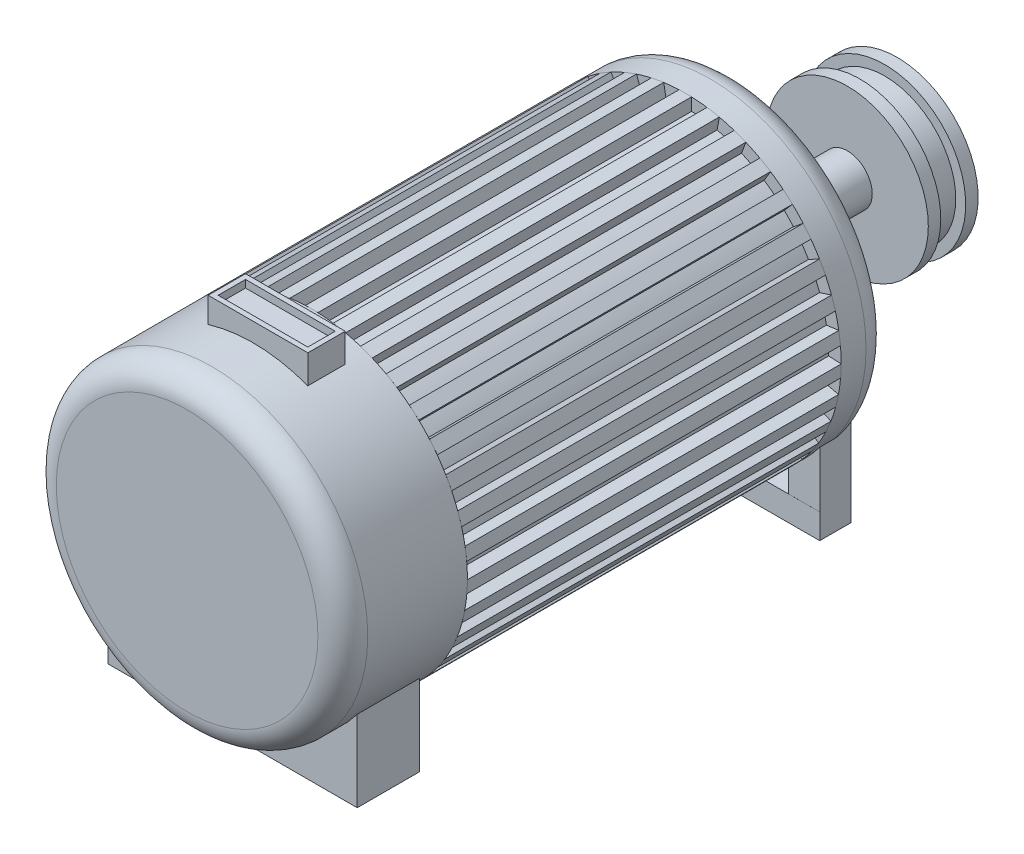
SolidWorks part; units mm, degrees
ref_plane "Front Plane" through (0, 0, 0) normal (0, 0, 1) x (1, 0, 0)
ref_plane "Top Plane" through (0, 0, 0) normal (0, 1, 0) x (1, 0, 0)
ref_plane "Right Plane" through (0, 0, 0) normal (1, 0, 0) x (0, 0, -1)
sketch "Sketch1" plane through (0, 0, 0) normal (0, 0, 1) x (1, 0, 0)
  line L0 (0.87, 6.1942) -> (1.362, 6.1049)
  line L1 (-0.25, 6.25) -> (0.25, 6.25)
  line L2 (0.25, 6.25) -> (0.25, 5.7446)
  line L3 (-0.25, 6.25) -> (-0.25, 5.7446)
  line L4 (0.87, 6.1942) -> (0.7797, 5.6969)
  line L5 (1.362, 6.1049) -> (1.2717, 5.6076)
  line L6 (1.962, 5.9393) -> (2.4302, 5.7636)
  line L7 (1.962, 5.9393) -> (1.7844, 5.4661)
  line L8 (2.4302, 5.7636) -> (2.2526, 5.2904)
  line L9 (2.991, 5.4935) -> (3.4202, 5.2371)
  line L10 (2.991, 5.4935) -> (2.7318, 5.0596)
  line L11 (3.4202, 5.2371) -> (3.161, 4.8032)
  line L12 (3.9238, 4.8712) -> (4.3004, 4.5422)
  line L13 (3.9238, 4.8712) -> (3.5913, 4.4906)
  line L14 (4.3004, 4.5422) -> (3.9678, 4.1616)
  line L15 (4.7306, 4.0923) -> (5.0423, 3.7014)
  line L16 (4.7306, 4.0923) -> (4.3354, 3.7771)
  line L17 (5.0423, 3.7014) -> (4.6472, 3.3862)
  line L18 (5.3853, 3.1818) -> (5.6222, 2.7415)
  line L19 (5.3853, 3.1818) -> (4.9402, 2.9423)
  line L20 (5.6222, 2.7415) -> (5.1771, 2.502)
  line L21 (5.8668, 2.1691) -> (6.0214, 1.6936)
  line L22 (5.8668, 2.1691) -> (5.3861, 2.0129)
  line L23 (6.0214, 1.6936) -> (5.5407, 1.5374)
  line L24 (6.1599, 1.0867) -> (6.227, 0.5912)
  line L25 (6.1599, 1.0867) -> (5.659, 1.0188)
  line L26 (6.227, 0.5912) -> (5.7261, 0.5234)
  line L27 (6.2549, -0.0307) -> (6.2325, -0.5302)
  line L28 (6.2549, -0.0307) -> (5.75, -0.008)
  line L29 (6.2325, -0.5302) -> (5.7276, -0.5075)
  line L30 (6.1489, -1.147) -> (6.0377, -1.6345)
  line L31 (6.1489, -1.147) -> (5.6562, -1.0346)
  line L32 (6.0377, -1.6345) -> (5.5449, -1.522)
  line L33 (5.8453, -2.2265) -> (5.6488, -2.6863)
  line L34 (5.8453, -2.2265) -> (5.3805, -2.0279)
  line L35 (5.6488, -2.6863) -> (5.184, -2.4876)
  line L36 (5.3538, -3.2345) -> (5.0784, -3.6517)
  line L37 (5.3538, -3.2345) -> (4.932, -2.956)
  line L38 (5.0784, -3.6517) -> (4.6565, -3.3733)
  line L39 (4.6902, -4.1384) -> (4.3447, -4.4998)
  line L40 (4.6902, -4.1384) -> (4.3249, -3.7892)
  line L41 (4.3447, -4.4998) -> (3.9794, -4.1506)
  line L42 (3.8759, -4.9094) -> (3.4714, -5.2033)
  line L43 (3.8759, -4.9094) -> (3.5788, -4.5005)
  line L44 (3.4714, -5.2033) -> (3.1743, -4.7944)
  line L45 (2.937, -5.5226) -> (2.4865, -5.7395)
  line L46 (2.937, -5.5226) -> (2.7177, -5.0672)
  line L47 (2.4865, -5.7395) -> (2.2672, -5.2841)
  line L48 (1.9037, -5.9583) -> (1.4217, -6.0913)
  line L49 (1.9037, -5.9583) -> (1.7693, -5.471)
  line L50 (1.4217, -6.0913) -> (1.2873, -5.6041)
  line L51 (0.8092, -6.2024) -> (0.3113, -6.2472)
  line L52 (0.8092, -6.2024) -> (0.7639, -5.699)
  line L53 (0.3113, -6.2472) -> (0.2659, -5.7438)
  line L54 (-0.3113, -6.2472) -> (-0.8092, -6.2024)
  line L55 (-0.3113, -6.2472) -> (-0.2659, -5.7438)
  line L56 (-0.8092, -6.2024) -> (-0.7639, -5.699)
  line L57 (-1.4217, -6.0913) -> (-1.9037, -5.9583)
  line L58 (-1.4217, -6.0913) -> (-1.2873, -5.6041)
  line L59 (-1.9037, -5.9583) -> (-1.7693, -5.471)
  line L60 (-2.4865, -5.7395) -> (-2.937, -5.5226)
  line L61 (-2.4865, -5.7395) -> (-2.2672, -5.2841)
  line L62 (-2.937, -5.5226) -> (-2.7177, -5.0672)
  line L63 (-3.4714, -5.2033) -> (-3.8759, -4.9094)
  line L64 (-3.4714, -5.2033) -> (-3.1743, -4.7944)
  line L65 (-3.8759, -4.9094) -> (-3.5788, -4.5005)
  line L66 (-4.3447, -4.4998) -> (-4.6902, -4.1384)
  line L67 (-4.3447, -4.4998) -> (-3.9794, -4.1506)
  line L68 (-4.6902, -4.1384) -> (-4.3249, -3.7892)
  line L69 (-5.0784, -3.6517) -> (-5.3538, -3.2345)
  line L70 (-5.0784, -3.6517) -> (-4.6565, -3.3733)
  line L71 (-5.3538, -3.2345) -> (-4.932, -2.956)
  line L72 (-5.6488, -2.6863) -> (-5.8453, -2.2265)
  line L73 (-5.6488, -2.6863) -> (-5.184, -2.4876)
  line L74 (-5.8453, -2.2265) -> (-5.3805, -2.0279)
  line L75 (-6.0377, -1.6345) -> (-6.1489, -1.147)
  line L76 (-6.0377, -1.6345) -> (-5.5449, -1.522)
  line L77 (-6.1489, -1.147) -> (-5.6562, -1.0346)
  line L78 (-6.2325, -0.5302) -> (-6.2549, -0.0307)
  line L79 (-6.2325, -0.5302) -> (-5.7276, -0.5075)
  line L80 (-6.2549, -0.0307) -> (-5.75, -0.008)
  line L81 (-6.227, 0.5912) -> (-6.1599, 1.0867)
  line L82 (-6.227, 0.5912) -> (-5.7261, 0.5234)
  line L83 (-6.1599, 1.0867) -> (-5.659, 1.0188)
  line L84 (-6.0214, 1.6936) -> (-5.8668, 2.1691)
  line L85 (-6.0214, 1.6936) -> (-5.5407, 1.5374)
  line L86 (-5.8668, 2.1691) -> (-5.3861, 2.0129)
  line L87 (-5.6222, 2.7415) -> (-5.3853, 3.1818)
  line L88 (-5.6222, 2.7415) -> (-5.1771, 2.502)
  line L89 (-5.3853, 3.1818) -> (-4.9402, 2.9423)
  line L90 (-5.0423, 3.7014) -> (-4.7306, 4.0923)
  line L91 (-5.0423, 3.7014) -> (-4.6472, 3.3862)
  line L92 (-4.7306, 4.0923) -> (-4.3354, 3.7771)
  line L93 (-4.3004, 4.5422) -> (-3.9238, 4.8712)
  line L94 (-4.3004, 4.5422) -> (-3.9678, 4.1616)
  line L95 (-3.9238, 4.8712) -> (-3.5913, 4.4906)
  line L96 (-3.4202, 5.2371) -> (-2.991, 5.4935)
  line L97 (-3.4202, 5.2371) -> (-3.161, 4.8032)
  line L98 (-2.991, 5.4935) -> (-2.7318, 5.0596)
  line L99 (-2.4302, 5.7636) -> (-1.962, 5.9393)
  line L100 (-2.4302, 5.7636) -> (-2.2526, 5.2904)
  line L101 (-1.962, 5.9393) -> (-1.7844, 5.4661)
  line L102 (-1.362, 6.1049) -> (-0.87, 6.1942)
  line L103 (-1.362, 6.1049) -> (-1.2717, 5.6076)
  line L104 (-0.87, 6.1942) -> (-0.7797, 5.6969)
  arc A0 (-0.25, 5.7446) -> (-0.7797, 5.6969) centre (0, 0) ccw
  arc A1 (-1.2717, 5.6076) -> (-1.7844, 5.4661) centre (0, 0) ccw
  arc A2 (-2.2526, 5.2904) -> (-2.7318, 5.0596) centre (0, 0) ccw
  arc A3 (-3.161, 4.8032) -> (-3.5913, 4.4906) centre (0, 0) ccw
  arc A4 (-3.9678, 4.1616) -> (-4.3354, 3.7771) centre (0, 0) ccw
  arc A5 (-4.6472, 3.3862) -> (-4.9402, 2.9423) centre (0, 0) ccw
  arc A6 (-5.1771, 2.502) -> (-5.3861, 2.0129) centre (0, 0) ccw
  arc A7 (0.7797, 5.6969) -> (0.25, 5.7446) centre (0, 0) ccw
  arc A8 (1.7844, 5.4661) -> (1.2717, 5.6076) centre (0, 0) ccw
  arc A9 (2.7318, 5.0596) -> (2.2526, 5.2904) centre (0, 0) ccw
  arc A10 (3.5913, 4.4906) -> (3.161, 4.8032) centre (0, 0) ccw
  arc A11 (4.3354, 3.7771) -> (3.9678, 4.1616) centre (0, 0) ccw
  arc A12 (4.9402, 2.9423) -> (4.6472, 3.3862) centre (0, 0) ccw
  arc A13 (5.3861, 2.0129) -> (5.1771, 2.502) centre (0, 0) ccw
  arc A14 (5.659, 1.0188) -> (5.5407, 1.5374) centre (0, 0) ccw
  arc A15 (5.75, -0.008) -> (5.7261, 0.5234) centre (0, 0) ccw
  arc A16 (5.6562, -1.0346) -> (5.7276, -0.5075) centre (0, 0) ccw
  arc A17 (5.3805, -2.0279) -> (5.5449, -1.522) centre (0, 0) ccw
  arc A18 (4.932, -2.956) -> (5.184, -2.4876) centre (0, 0) ccw
  arc A19 (4.3249, -3.7892) -> (4.6565, -3.3733) centre (0, 0) ccw
  arc A20 (3.5788, -4.5005) -> (3.9794, -4.1506) centre (0, 0) ccw
  arc A21 (2.7177, -5.0672) -> (3.1743, -4.7944) centre (0, 0) ccw
  arc A22 (1.7693, -5.471) -> (2.2672, -5.2841) centre (0, 0) ccw
  arc A23 (0.7639, -5.699) -> (1.2873, -5.6041) centre (0, 0) ccw
  arc A24 (-0.2659, -5.7438) -> (0.2659, -5.7438) centre (0, 0) ccw
  arc A25 (-1.2873, -5.6041) -> (-0.7639, -5.699) centre (0, 0) ccw
  arc A26 (-2.2672, -5.2841) -> (-1.7693, -5.471) centre (0, 0) ccw
  arc A27 (-3.1743, -4.7944) -> (-2.7177, -5.0672) centre (0, 0) ccw
  arc A28 (-3.9794, -4.1506) -> (-3.5788, -4.5005) centre (0, 0) ccw
  arc A29 (-4.6565, -3.3733) -> (-4.3249, -3.7892) centre (0, 0) ccw
  arc A30 (-5.184, -2.4876) -> (-4.932, -2.956) centre (0, 0) ccw
  arc A31 (-5.5449, -1.522) -> (-5.3805, -2.0279) centre (0, 0) ccw
  arc A32 (-5.7276, -0.5075) -> (-5.6562, -1.0346) centre (0, 0) ccw
  arc A33 (-5.7261, 0.5234) -> (-5.75, -0.008) centre (0, 0) ccw
  arc A34 (-5.5407, 1.5374) -> (-5.659, 1.0188) centre (0, 0) ccw
  point P9 (0, 6.25)
  point P10 (0, 6.25)
  point P147 (0, 0)
  dimension "D1" = 0.5
  dimension "D2" = 35
extrude "Boss-Extrude1" add sketch "Sketch1" against normal blind 15
sketch "Sketch2" plane through (0, 0, 0) normal (0, 0, 1) x (1, 0, 0)
  circle A0 centre (0, 0) radius 6.25
extrude "Boss-Extrude2" add sketch "Sketch2" along normal blind 5
fillet "Fillet1" radius 1 1 edges at (6.25, 0, 5)
sketch "Sketch3" plane through (0, 0, 0) normal (0, 1, 0) x (1, 0, 0)
  line L1 (-1.8048, -0.8495) -> (2.1952, -0.8495)
  line L2 (-1.8048, -0.8495) -> (-1.8048, -2.3495)
  line L3 (-1.8048, -2.3495) -> (2.1952, -2.3495)
  line L4 (2.1952, -0.8495) -> (2.1952, -2.3495)
  point P0 (0, -1.5995)
  dimension "D1" = 4
  dimension "D2" = 1.5
  dimension "D3" = 0
extrude "Boss-Extrude3" add sketch "Sketch3" along normal blind 7
sketch "Sketch4" plane through (0, 7, 0) normal (0, 1, 0) x (1, 0, 0)
  line L0 (-1.6048, -1.0495) -> (1.9952, -1.0495)
  line L3 (1.9952, -1.0495) -> (1.9952, -2.1495)
  line L4 (1.9952, -2.1495) -> (-1.6048, -2.1495)
  line L5 (-1.6048, -2.1495) -> (-1.6048, -1.0495)
  dimension "D1" = 3.6
  dimension "D2" = 1.1
extrude "Cut-Extrude1" cut sketch "Sketch4" against normal blind 0.3
sketch "Sketch5" plane through (0, 0, 0) normal (0, 1, 0) x (1, 0, 0)
  line L2 (-5, -0.6723) -> (5, -0.6723)
  line L3 (-5, -0.6723) -> (-5, -3.1723)
  line L4 (-5, -3.1723) -> (5, -3.1723)
  line L5 (5, -0.6723) -> (5, -3.1723)
  point P4 (0, -1.9223)
  dimension "D1" = 2.5
  dimension "D2" = 10
extrude "Boss-Extrude4" add sketch "Sketch5" against normal blind 7
sketch "Sketch6" plane through (0, -7, 0) normal (0, -1, 0) x (-1, 0, 0)
  circle A0 centre (4, -1.9223) radius 0.5
  circle A1 centre (-4, -1.9223) radius 0.5
extrude "Cut-Extrude2" cut sketch "Sketch6" against normal blind 3
sketch "Sketch7" plane through (0, 0, -15) normal (0, 0, -1) x (-1, 0, 0)
  circle A0 centre (0, 0) radius 6.25
  dimension "D1" = 12.5
extrude "Boss-Extrude5" add sketch "Sketch7" along normal blind 2
fillet "Fillet2" radius 1 1 edges at (-6.25, 0, -17)
sketch "Sketch8" plane through (0, 0, -17) normal (0, 0, -1) x (-1, 0, 0)
  circle A0 centre (0, 0) radius 2.5
  circle A1 centre (0, 0) radius 1.25
extrude "Boss-Extrude6" add sketch "Sketch8" along normal blind 1
sketch "Sketch9" plane through (0, 0, -17) normal (0, 0, -1) x (-1, 0, 0)
  circle A0 centre (0, 0) radius 1
extrude "Boss-Extrude7" add sketch "Sketch9" along normal blind 5
sketch "Sketch10" plane through (0, 0, 0) normal (0, 1, 0) x (1, 0, 0)
  line L4 (-5, 16.625) -> (-3.75, 16.625)
  line L5 (-5, 16.625) -> (-5, 15.375)
  line L6 (-5, 15.375) -> (-3.75, 15.375)
  line L7 (-3.75, 16.625) -> (-3.75, 15.375)
  line L10 (3.75, 16.6427) -> (5, 16.6427)
  line L11 (3.75, 16.6427) -> (3.75, 15.3927)
  line L12 (3.75, 15.3927) -> (5, 15.3927)
  line L13 (5, 16.6427) -> (5, 15.3927)
  dimension "D3" = 1.25
  dimension "D4" = 1.25
extrude "Boss-Extrude10" add sketch "Sketch10" against normal blind 7
sketch "Sketch14" plane through (0, -7, 0) normal (0, -1, 0) x (1, 0, 0)
  line L0 (-5, -15.375) -> (5, -15.3927)
  line L1 (5, -15.3927) -> (5, -16.6427)
  line L2 (5, -16.6427) -> (-5, -16.625)
  line L3 (-5, -16.625) -> (-5, -15.375)
extrude "Boss-Extrude11" add sketch "Sketch14" against normal blind 1
sketch "Sketch15" plane through (0, -7, 0) normal (0, -1, 0) x (1, 0, 0)
  line L6 (6.25, -16) -> (-6.25, -16) construction
  circle A0 centre (-4, -16) radius 0.5
  circle A1 centre (4, -16) radius 0.5
extrude "Cut-Extrude4" cut sketch "Sketch15" against normal blind 1
sketch "Sketch16" plane through (0, 0, -22) normal (0, 0, -1) x (-1, 0, 0)
  circle A0 centre (0, 0) radius 2.85
  dimension "D1" = 5.7
extrude "Boss-Extrude12" add sketch "Sketch16" along normal blind 1
sketch "Sketch17" plane through (0, 0, -23) normal (0, 0, -1) x (-1, 0, 0)
  circle A0 centre (0, 0) radius 3.25
  dimension "D1" = 6.5
extrude "Boss-Extrude13" add sketch "Sketch17" along normal blind 0.5
sketch "Sketch18" plane through (0, 0, -22) normal (0, 0, 1) x (1, 0, 0)
  circle A0 centre (0, 0) radius 3.25
extrude "Boss-Extrude14" add sketch "Sketch18" along normal blind 0.5
